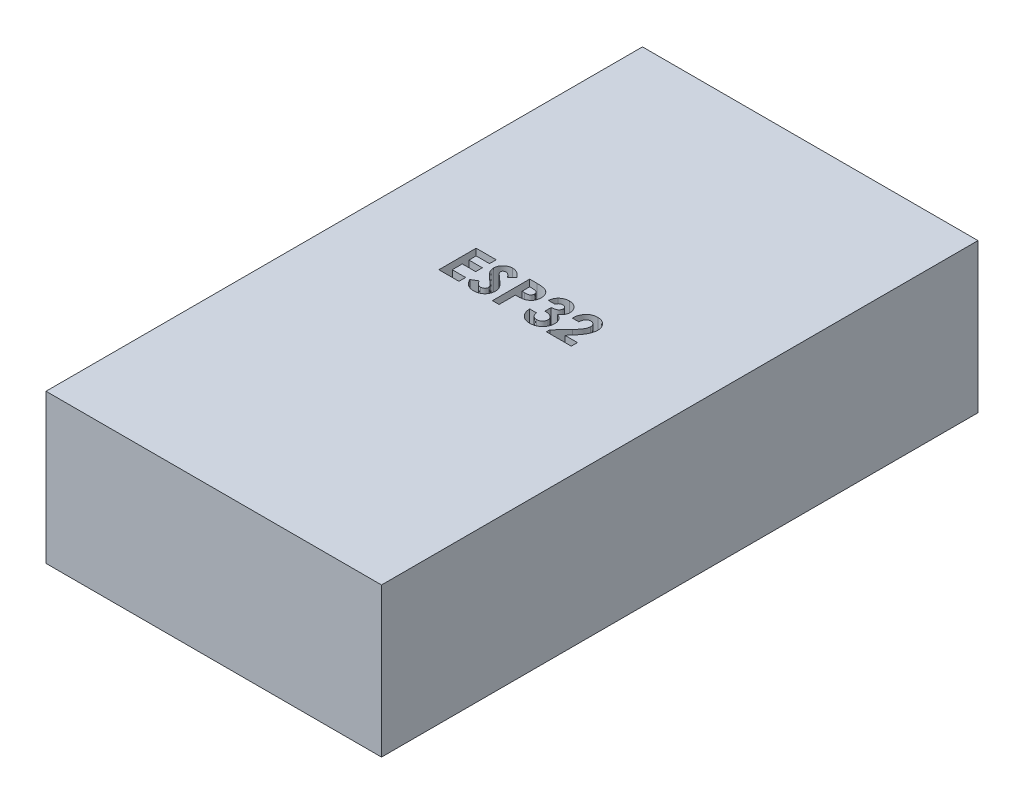
SolidWorks part; units mm, degrees
material "PVC Rigid"
ref_plane "Front Plane" through (0, 0, 0) normal (0, 0, 1) x (1, 0, 0)
ref_plane "Top Plane" through (0, 0, 0) normal (0, 1, 0) x (1, 0, 0)
ref_plane "Right Plane" through (0, 0, 0) normal (1, 0, 0) x (0, 0, -1)
sketch "Sketch1" plane through (0, 0, 0) normal (0, 1, 0) x (1, 0, 0)
  line L1 (-14.2875, -25.4) -> (14.2875, -25.4)
  line L2 (-14.2875, -25.4) -> (-14.2875, 25.4)
  line L3 (-14.2875, 25.4) -> (14.2875, 25.4)
  line L4 (14.2875, -25.4) -> (14.2875, 25.4)
  line L5 (-14.2875, -25.4) -> (14.2875, 25.4) construction
  line L6 (-14.2875, 25.4) -> (14.2875, -25.4) construction
  point P0 (0, 0)
  dimension "D1" = 28.575
  dimension "D2" = 50.8
extrude "Boss-Extrude1" add sketch "Sketch1" along normal blind 12.7
sketch "Sketch3" plane through (0, 12.7, 0) normal (0, 1, 0) x (1, 0, 0)
  text T0 "<b>ESP32</b>"
extrude "Cut-Extrude1" cut sketch "Sketch3" against normal blind 2.54
